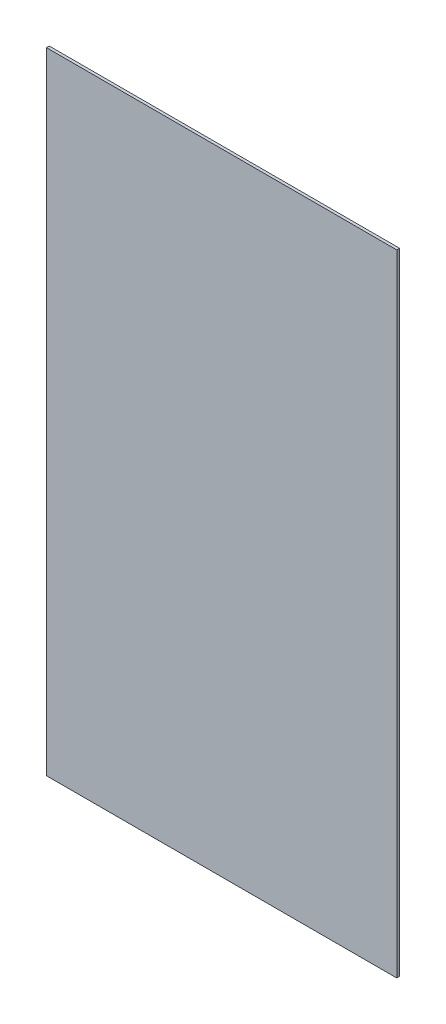
SolidWorks part; units mm, degrees
ref_plane "정면" through (0, 0, 0) normal (0, 0, 1) x (1, 0, 0)
ref_plane "윗면" through (0, 0, 0) normal (0, 1, 0) x (1, 0, 0)
ref_plane "우측면" through (0, 0, 0) normal (1, 0, 0) x (0, 0, -1)
sketch "스케치1" plane through (0, 0, 0) normal (0, 0, 1) x (1, 0, 0)
  line L1 (0, 0) -> (25, 0)
  line L2 (0, 0) -> (0, 45)
  line L3 (0, 45) -> (25, 45)
  line L4 (25, 0) -> (25, 45)
  dimension "D1" = 45
  dimension "D2" = 25
extrude "보스-돌출1" add sketch "스케치1" along normal blind 0.2
